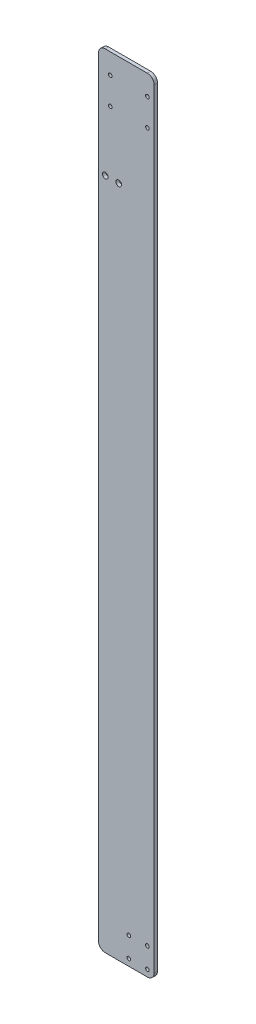
SolidWorks part; units mm, degrees
material "PC High Viscosity"
ref_plane "Front Plane" through (0, 0, 0) normal (0, 0, 1) x (1, 0, 0)
ref_plane "Top Plane" through (0, 0, 0) normal (0, 1, 0) x (1, 0, 0)
ref_plane "Right Plane" through (0, 0, 0) normal (1, 0, 0) x (0, 0, -1)
sketch "Sketch1" plane through (0, 0, 0) normal (0, 0, 1) x (1, 0, 0)
  line L1 (12.7, 0) -> (92.075, 0)
  line L2 (0, 12.7) -> (0, 1460.5)
  line L3 (12.7, 1473.2) -> (92.075, 1473.2)
  line L4 (104.775, 12.7) -> (104.775, 1460.5)
  circle A0 centre (92.075, 1435.1) radius 3.429
  circle A1 centre (92.075, 1384.3) radius 3.429
  circle A2 centre (22.225, 1384.3) radius 3.429
  circle A3 centre (22.225, 1435.1) radius 3.429
  circle A4 centre (92.075, 50.8) radius 3.429
  circle A5 centre (57.15, 50.8) radius 3.429
  circle A6 centre (57.15, 12.7) radius 3.429
  circle A7 centre (92.075, 12.7) radius 3.429
  arc A8 (0, 1460.5) -> (12.7, 1473.2) centre (12.7, 1460.5) cw
  arc A9 (92.075, 1473.2) -> (104.775, 1460.5) centre (92.075, 1460.5) cw
  arc A10 (92.075, 0) -> (104.775, 12.7) centre (92.075, 12.7) ccw
  arc A11 (12.7, 0) -> (0, 12.7) centre (12.7, 12.7) cw
  circle A12 centre (38.1, 1266.825) radius 5.3578
  circle A13 centre (12.7, 1266.825) radius 5.3578
  point P23 (0, 1473.2)
  point P28 (104.775, 0)
  point P31 (0, 0)
  dimension "D4" = 69.85
  dimension "D5" = 50.8
  dimension "D6" = 50.8
  dimension "D7" = 69.85
  dimension "D8" = 6.858
  dimension "D9" = 6.858
  dimension "D10" = 6.858
  dimension "D11" = 6.858
  dimension "D15" = 12.7
  dimension "D16" = 6.858
  dimension "D23" = 6.858
  dimension "D24" = 6.858
  dimension "D25" = 6.858
  dimension "D27" = 10.7156
  dimension "D28" = 10.7156
  dimension "D32" = 1266.825
  dimension "D1" = 104.775
  dimension "D2" = 1473.2
  dimension "D3" = 12.7
  dimension "D12" = 38.1
  dimension "D13" = 12.7
  dimension "D14" = 38.1
  dimension "D17" = 12.7
  dimension "D18" = 34.925
  dimension "D19" = 34.925
  dimension "D20" = 12.7
  dimension "D21" = 38.1
  dimension "D22" = 38.1
  dimension "D26" = 12.7
  dimension "D29" = 12.7
  dimension "D30" = 25.4
  dimension "D33" = 12.7
extrude "Boss-Extrude1" add sketch "Sketch1" along normal blind 6.35
